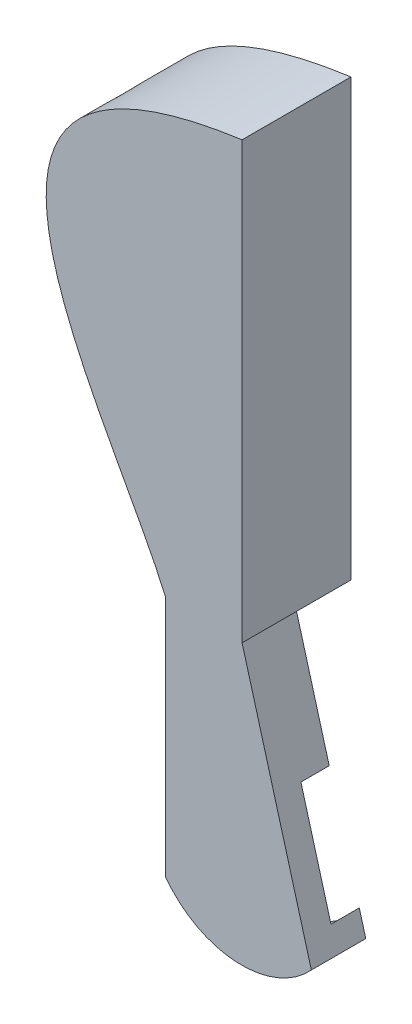
SolidWorks part; units mm, degrees
ref_plane "Front Plane" through (0, 0, 0) normal (0, 0, 1) x (1, 0, 0)
ref_plane "Top Plane" through (0, 0, 0) normal (0, 1, 0) x (1, 0, 0)
ref_plane "Right Plane" through (0, 0, 0) normal (1, 0, 0) x (0, 0, -1)
sketch "Sketch1" plane through (0, 0, 0) normal (0, 0, 1) x (1, 0, 0)
  line L0 (0.2218, 84.8283) -> (0.2207, 284.8283)
  line L1 (35, -85.625) -> (-35, -85.625)
  line L4 (-35, -85.625) -> (-35, 85.625)
  line L5 (35, -85.625) -> (-35, 85.625) construction
  line L6 (35, 85.625) -> (-35, -85.625) construction
  line L7 (0.2218, 84.8283) -> (35, -40.1019)
  line L8 (35, -40.1019) -> (35, -85.625)
  spline S0 degree 3 poles (0.2207, 284.8283) (-159.9787, 262.6066) (-63.0007, 150.139) (-35, 85.625) knots 0 0 0 0 1 1 1 1
  point P1 (0, 0)
  dimension "D1" = 70
  dimension "D2" = 200
extrude "Boss-Extrude1" add sketch "Sketch1" along normal blind 50
sketch "Sketch2" plane through (0, 0, 50) normal (0, 0, 1) x (1, 0, 0)
  circle A0 centre (0, 0) radius 20
sketch "Sketch3" plane through (22.122, 6.1583, 0) normal (0.9634, 0.2682, 0) x (0, 0, -1)
  line L0 (-50, 81.6614) -> (0, 81.6614) construction
  line L1 (-25, 81.6614) -> (-25, -107.2994)
  line L2 (-25, -107.2994) -> (41.3764, -107.2994)
  line L5 (41.3764, -107.2994) -> (41.3764, 81.6614)
  line L6 (41.3764, 81.6614) -> (-25, 81.6614)
extrude "Cut-Extrude1" cut sketch "Sketch3" against normal through all
sketch "Sketch4" plane through (0, 0, 25) normal (0, 0, -1) x (-1, 0, 0)
  circle A0 centre (0, 0) radius 34.5
extrude "Cut-Extrude2" cut sketch "Sketch4" against normal blind 13
sketch "Sketch5" plane through (0, 0, 25) normal (0, 0, -1) x (-1, 0, 0)
  line L1 (35, 75.0232) -> (35, -85.625) construction
  line L2 (35, -40.1019) -> (35, -85.625)
  line L3 (35, -85.625) -> (-35, -85.625)
  line L4 (-35, -85.625) -> (-35, -40.1019)
  line L5 (-35, -40.1019) -> (-32.0136, -29.374)
  line L6 (-29.0271, -18.6461) -> (-35, -40.1019) construction
  line L7 (35, -25.743) -> (35, -40.1019)
  arc A0 (-32.0136, -29.374) -> (35, -25.743) centre (0, 0) ccw
extrude "Cut-Extrude3" cut sketch "Sketch5" against normal through all
